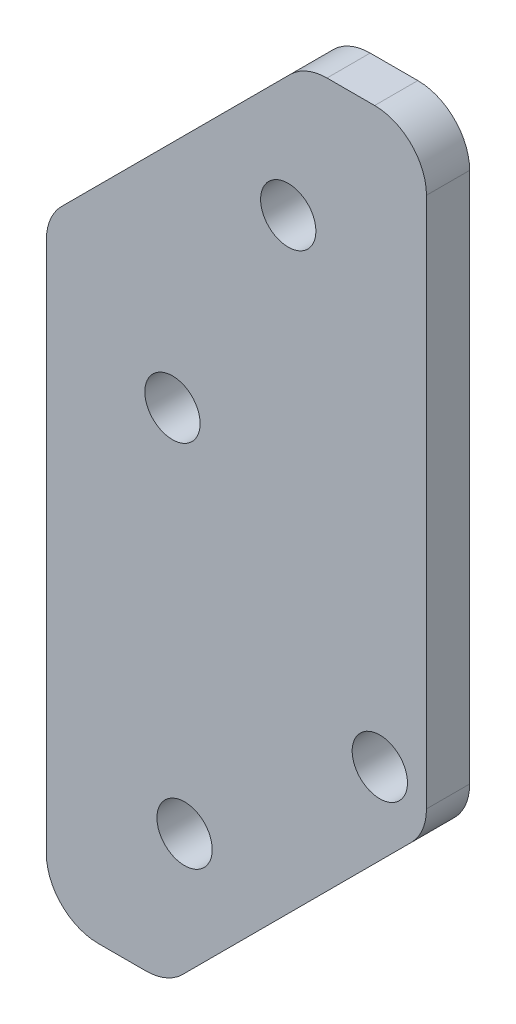
SolidWorks part; units mm, degrees
material "Thornel Mat VMA"
ref_plane "前视基准面" through (0, 0, 0) normal (0, 0, 1) x (1, 0, 0)
ref_plane "上视基准面" through (0, 0, 0) normal (0, 1, 0) x (1, 0, 0)
ref_plane "右视基准面" through (0, 0, 0) normal (1, 0, 0) x (0, 0, -1)
sketch "草图1" plane through (0, 0, 0) normal (0, 0, 1) x (1, 0, 0)
  line L0 (11, 25) -> (11, -25)
  line L1 (-3, 17) -> (3, 17) construction
  line L2 (-3, 17) -> (-3, -17) construction
  line L3 (-3, -17) -> (3, -17) construction
  line L4 (3, 17) -> (3, -17) construction
  line L5 (-3, 17) -> (3, -17) construction
  line L6 (-3, -17) -> (3, 17) construction
  line L7 (-11, -25) -> (11, -25)
  line L8 (-11, 25) -> (-11, -25)
  line L9 (-11, 25) -> (11, 25)
  circle A0 centre (-3, -17) radius 1.6
  circle A1 centre (3, 17) radius 1.6
  circle A2 centre (-3.7, 4) radius 1.6
  circle A3 centre (8.3, -8) radius 1.6
  point P0 (0, 0)
  point P16 (0, 0)
  dimension "D4" = 3.2
  dimension "D5" = 3.2
  dimension "D1" = 6
  dimension "D2" = 34
  dimension "D3" = 8
extrude "凸台-拉伸1" add sketch "草图1" along normal blind 2.5
chamfer "倒角1" distance 15 angle 45 2 edges at (-11, 25, 1.25) (11, -25, 1.25)
fillet "圆角1" radius 3 6 edges at (11, 25, 1.25) (11, -10, 1.25) (-4, -25, 1.25) (-11, 10, 1.25) (4, 25, 1.25) (-11, -25, 1.25)
